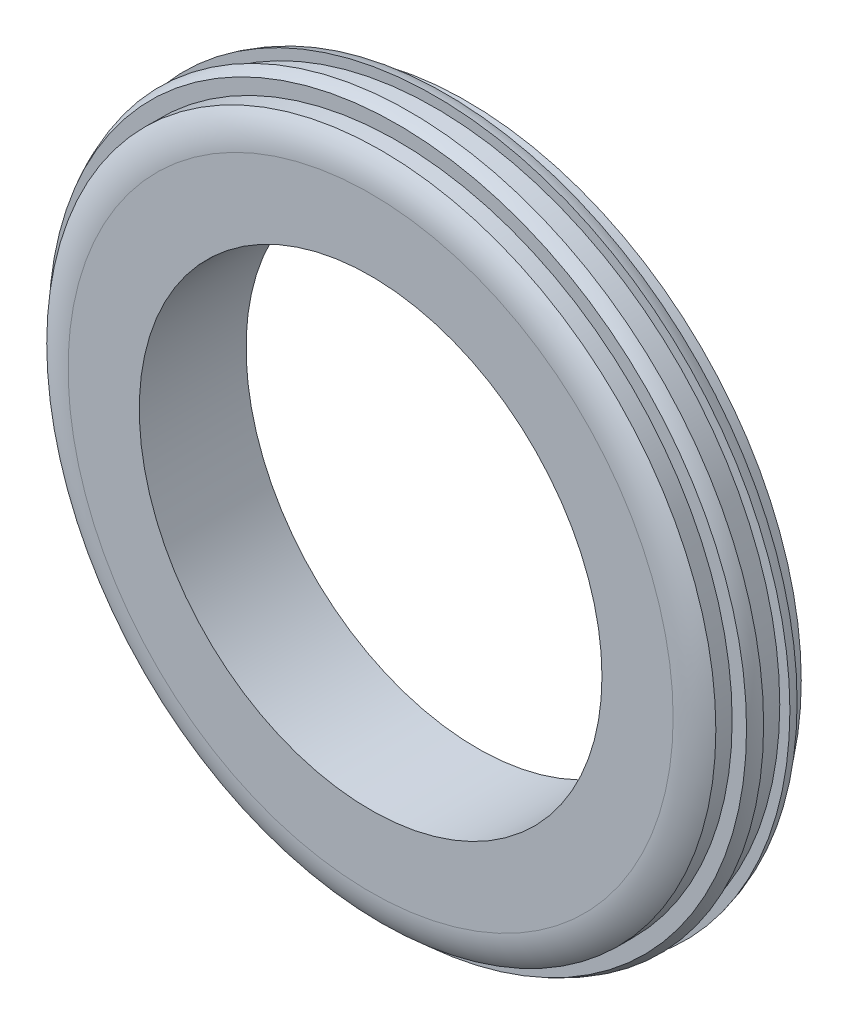
SolidWorks part; units mm, degrees
ref_plane "Front Plane" through (0, 0, 0) normal (0, 0, 1) x (1, 0, 0)
ref_plane "Top Plane" through (0, 0, 0) normal (0, 1, 0) x (1, 0, 0)
ref_plane "Right Plane" through (0, 0, 0) normal (1, 0, 0) x (0, 0, -1)
sketch "Sketch2" plane through (0, 0, 0) normal (1, 0, 0) x (0, 0, -1)
  line L0 (-102.5784, 0) -> (170.0348, 0) construction
  line L2 (-33.9024, 170) -> (-33.9024, 130)
  line L3 (-33.9024, 130) -> (26.0976, 130)
  line L4 (26.0976, 170) -> (26.0976, 130)
  line L5 (-33.9024, 170) -> (26.0976, 130) construction
  line L6 (-33.9024, 130) -> (26.0976, 170) construction
  arc A0 (-33.9024, 170) -> (26.0976, 170) centre (-3.9024, 170) cw
  point P0 (-3.9024, 150)
  point P9 (-3.9024, 130)
  dimension "D1" = 150
  dimension "D2" = 30
  dimension "D3" = 40
revolve "Revolve1" add sketch "Sketch2" angle 360 about L0
sketch "Sketch3" plane through (0, 0, 0) normal (1, 0, 0) x (0, 0, -1)
  line L0 (-101.3639, 0) -> (171.565, 0) construction
  line L1 (-11.949, 320.2622) -> (2.3702, 320.2622)
  line L2 (-11.949, 320.2622) -> (-11.949, 193.65)
  line L3 (-11.949, 193.65) -> (2.3702, 193.65)
  line L4 (2.3702, 320.2622) -> (2.3702, 193.65)
  line L5 (-11.949, 320.2622) -> (2.3702, 193.65) construction
  line L6 (-11.949, 193.65) -> (2.3702, 320.2622) construction
  line L7 (-48.8776, 373.3941) -> (-18.7318, 373.3941)
  line L8 (-48.8776, 373.3941) -> (-48.8776, 187.9977)
  line L9 (-48.8776, 187.9977) -> (-18.7318, 187.9977)
  line L10 (-18.7318, 373.3941) -> (-18.7318, 187.9977)
  line L11 (-48.8776, 373.3941) -> (-18.7318, 187.9977) construction
  line L12 (-48.8776, 187.9977) -> (-18.7318, 373.3941) construction
  line L13 (20.4577, 410.3227) -> (8.3994, 410.3227)
  line L14 (20.4577, 410.3227) -> (20.4577, 187.9977)
  line L15 (20.4577, 187.9977) -> (8.3994, 187.9977)
  line L16 (8.3994, 410.3227) -> (8.3994, 187.9977)
  line L17 (20.4577, 410.3227) -> (8.3994, 187.9977) construction
  line L18 (20.4577, 187.9977) -> (8.3994, 410.3227) construction
  point P0 (-4.7894, 256.9561)
  point P5 (-33.8047, 280.6959)
  point P10 (14.4285, 299.1602)
revolve "Cut-Revolve1" cut sketch "Sketch3" angle 360 about L0
